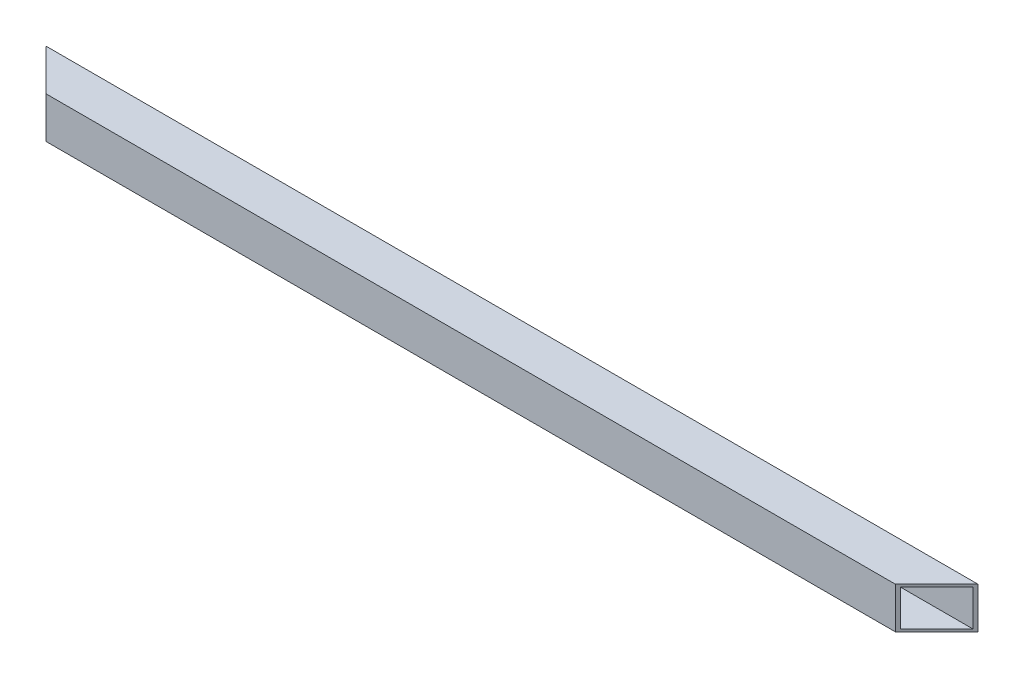
SolidWorks part; units mm, degrees
ref_plane "Front Plane" through (0, 0, 0) normal (0, 0, 1) x (1, 0, 0)
ref_plane "Top Plane" through (0, 0, 0) normal (0, 1, 0) x (1, 0, 0)
ref_plane "Right Plane" through (0, 0, 0) normal (1, 0, 0) x (0, 0, -1)
sketch "Sketch1" plane through (0, 0, 0) normal (1, 0, 0) x (0, 0, -1)
  line L0 (-9.525, -9.525) -> (9.525, -9.525)
  line L1 (-9.525, -9.525) -> (-9.525, 9.525)
  line L2 (-9.525, 9.525) -> (9.525, 9.525)
  line L3 (9.525, -9.525) -> (9.525, 9.525)
  line L4 (-9.525, -9.525) -> (9.525, 9.525) construction
  line L5 (-9.525, 9.525) -> (9.525, -9.525) construction
  point P0 (0, 0)
  point P5 (0, 9.525)
  point P6 (-9.525, 0)
  dimension "D1" = 19.05
extrude "Boss-Extrude1" add sketch "Sketch1" along normal mid plane 430
sketch "Sketch2" plane through (-215, 0, 0) normal (-1, 0, 0) x (0, 0, 1)
  line L8 (-8.325, 8.325) -> (-8.325, -8.325)
  line L9 (-8.325, -8.325) -> (8.325, -8.325)
  line L10 (8.325, -8.325) -> (8.325, 8.325)
  line L11 (8.325, 8.325) -> (-8.325, 8.325)
  line L12 (-8.325, 8.325) -> (-8.325, -8.325)
  line L13 (-8.325, -8.325) -> (8.325, -8.325)
  line L14 (8.325, -8.325) -> (8.325, 8.325)
  line L15 (8.325, 8.325) -> (-8.325, 8.325)
  dimension "D1" = 1.2
extrude "Cut-Extrude1" cut sketch "Sketch2" against normal through all
sketch "Sketch3" plane through (0, 0, 0) normal (0, 1, 0) x (1, 0, 0)
  line L0 (0, 53.1704) -> (0, -53.1704) construction
  line L1 (-215, 9.525) -> (-215, -9.525)
  line L2 (-215, -9.525) -> (-195.95, -9.525)
  line L3 (215, -9.525) -> (-215, -9.525) construction
  line L4 (-195.95, -9.525) -> (-215, 9.525)
  line L5 (215, -9.525) -> (195.95, -9.525)
  line L6 (215, 9.525) -> (215, -9.525)
  line L7 (195.95, -9.525) -> (215, 9.525)
  point P2 (0, 0)
extrude "Cut-Extrude2" cut sketch "Sketch3" against normal through all both and the other way through all
